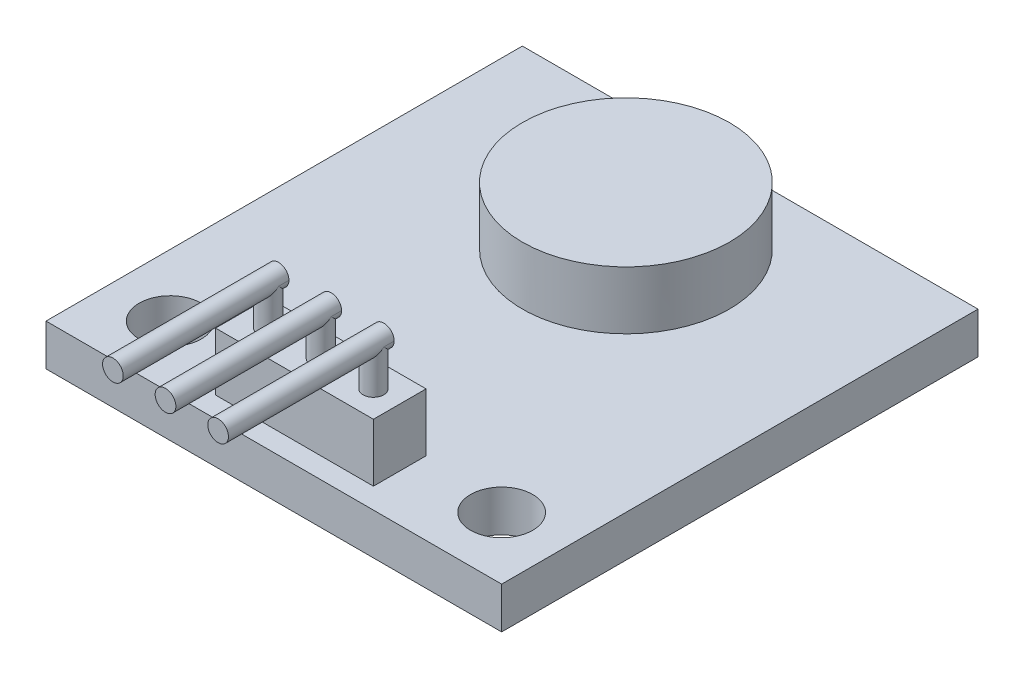
SolidWorks part; units mm, degrees
ref_plane "前视基准面" through (0, 0, 0) normal (0, 0, 1) x (1, 0, 0)
ref_plane "上视基准面" through (0, 0, 0) normal (0, 1, 0) x (1, 0, 0)
ref_plane "右视基准面" through (0, 0, 0) normal (1, 0, 0) x (0, 0, -1)
sketch "草图1" plane through (0, 0, 0) normal (0, 1, 0) x (1, 0, 0)
  line L0 (11, 0) -> (11, 31.6627) construction
  line L1 (0, 0) -> (22, 0)
  line L2 (0, 0) -> (0, 23)
  line L3 (0, 23) -> (22, 23)
  line L4 (22, 0) -> (22, 23)
  circle A0 centre (19, 3) radius 1.5
  circle A1 centre (3, 3) radius 1.5
  dimension "D3" = 16
  dimension "D4" = 3
  dimension "D1" = 22
  dimension "D2" = 23
  dimension "D5" = 3
extrude "凸台-拉伸1" add sketch "草图1" along normal blind 2
sketch "草图2" plane through (0, 2, 0) normal (0, 1, 0) x (1, 0, 0)
  line L0 (11, 0) -> (11, 24.0788) construction
  line L1 (0, 0) -> (22, 0) construction
  line L2 (22, 23) -> (0, 23) construction
  line L3 (7.19, 3.54) -> (14.81, 3.54)
  line L4 (14.81, 3.54) -> (14.81, 1)
  line L5 (14.81, 1) -> (7.19, 1)
  line L6 (7.19, 3.54) -> (7.19, 1)
  circle A0 centre (11, 17) radius 5
  point P13 (11, 1)
  point P14 (11, 3.54)
  dimension "D1" = 10
  dimension "D2" = 6
  dimension "D3" = 7.62
  dimension "D4" = 2.54
  dimension "D5" = 1
extrude "凸台-拉伸2" add sketch "草图2" along normal blind 2.8
sketch "草图3" plane through (0, 4.8, 0) normal (0, 1, 0) x (1, 0, 0)
  line L0 (7.19, 2.27) -> (14.81, 2.27) construction
  line L1 (7.19, 3.54) -> (7.19, 1) construction
  line L2 (14.81, 1) -> (14.81, 3.54) construction
  line L3 (11, 2.27) -> (11, -1.2709) construction
  circle A0 centre (13.54, 2.27) radius 0.5
  circle A1 centre (11, 2.27) radius 0.5
  circle A2 centre (8.46, 2.27) radius 0.5
  dimension "D1" = 2.54
  dimension "D2" = 1
  dimension "D3" = 1
extrude "凸台-拉伸3" add sketch "草图3" along normal blind 2
sketch "草图4" plane through (0, 0, -1) normal (0, 0, 1) x (1, 0, 0)
  line L0 (8.96, 6.8) -> (7.96, 6.8) construction
  line L1 (11.5, 6.8) -> (10.5, 6.8) construction
  line L2 (14.04, 6.8) -> (13.04, 6.8) construction
  circle A0 centre (8.46, 6.8) radius 0.5
  circle A1 centre (11, 6.8) radius 0.5
  circle A2 centre (13.54, 6.8) radius 0.5
extrude "凸台-拉伸4" add sketch "草图4" along normal blind 8 from offset 1.77
